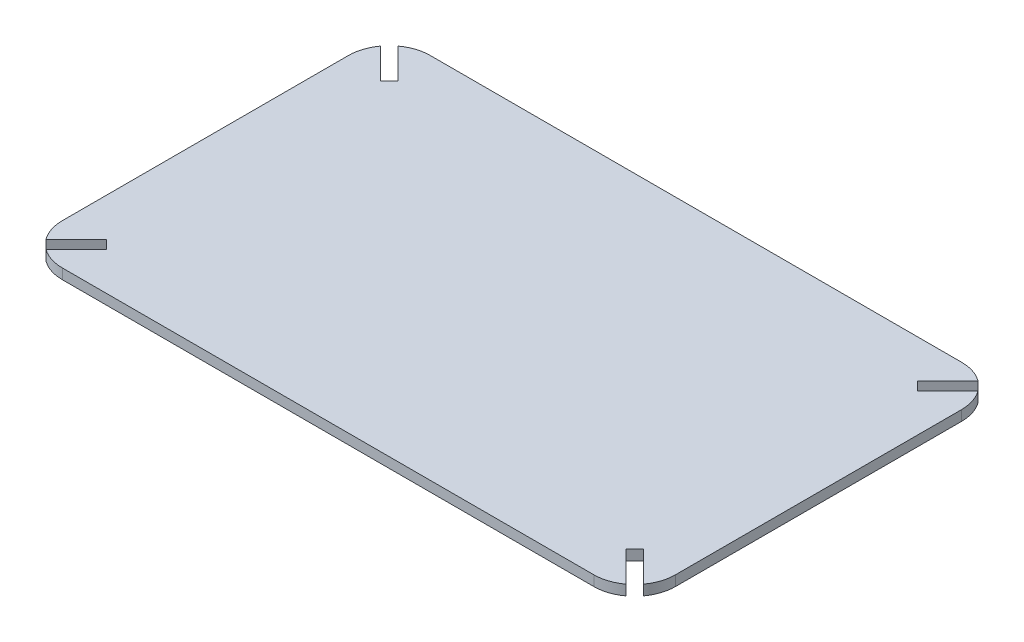
SolidWorks part; units mm, degrees
ref_plane "Front Plane" through (0, 0, 0) normal (0, 0, 1) x (1, 0, 0)
ref_plane "Top Plane" through (0, 0, 0) normal (0, 1, 0) x (1, 0, 0)
ref_plane "Right Plane" through (0, 0, 0) normal (1, 0, 0) x (0, 0, -1)
sketch "Sketch1" plane through (0, 0, 0) normal (0, 1, 0) x (1, 0, 0)
  line L1 (-165.1, -114.3) -> (165.1, -114.3)
  line L2 (-190.5, -88.9) -> (-190.5, 88.9)
  line L3 (-165.1, 114.3) -> (165.1, 114.3)
  line L4 (190.5, -88.9) -> (190.5, 88.9)
  line L5 (-190.5, -114.3) -> (190.5, 114.3) construction
  line L6 (-190.5, 114.3) -> (190.5, -114.3) construction
  arc A0 (-165.1, -114.3) -> (-190.5, -88.9) centre (-165.1, -88.9) cw
  arc A1 (165.1, -114.3) -> (190.5, -88.9) centre (165.1, -88.9) ccw
  arc A2 (165.1, 114.3) -> (190.5, 88.9) centre (165.1, 88.9) cw
  arc A3 (-190.5, 88.9) -> (-165.1, 114.3) centre (-165.1, 88.9) cw
  point P0 (0, 0)
  dimension "D3" = 25.4
  dimension "D1" = 228.6
  dimension "D2" = 381
extrude "Base Support" add sketch "Sketch1" along normal blind 6.35
sketch "Sketch2" plane through (0, 0, 0) normal (0, 1, 0) x (1, 0, 0)
  line L0 (-183.0605, -106.8605) -> (-190.996, -114.796) construction
  line L1 (-180.1632, -109.3514) -> (-161.3047, -90.4928)
  line L2 (-161.3047, -90.4928) -> (-166.6928, -85.1047)
  line L3 (-166.6928, -85.1047) -> (-185.5514, -103.9632)
  line L4 (0, 0) -> (0, -94.4406) construction
  line L5 (0, 0) -> (-78.1343, 0) construction
  line L6 (161.3047, -90.4928) -> (166.6928, -85.1047)
  line L7 (166.6928, -85.1047) -> (185.5514, -103.9632)
  line L8 (180.1632, -109.3514) -> (161.3047, -90.4928)
  line L9 (180.1632, 109.3514) -> (161.3047, 90.4928)
  line L10 (166.6928, 85.1047) -> (185.5514, 103.9632)
  line L11 (161.3047, 90.4928) -> (166.6928, 85.1047)
  line L12 (-166.6928, 85.1047) -> (-185.5514, 103.9632)
  line L13 (-161.3047, 90.4928) -> (-166.6928, 85.1047)
  line L14 (-180.1632, 109.3514) -> (-161.3047, 90.4928)
  arc A0 (-190.5, -88.9) -> (-165.1, -114.3) centre (-165.1, -88.9) ccw construction
  arc A1 (-185.5514, -103.9632) -> (-180.1632, -109.3514) centre (-165.1, -88.9) ccw
  arc A2 (185.5514, -103.9632) -> (180.1632, -109.3514) centre (165.1, -88.9) cw
  arc A3 (185.5514, 103.9632) -> (180.1632, 109.3514) centre (165.1, 88.9) ccw
  arc A4 (-185.5514, 103.9632) -> (-180.1632, 109.3514) centre (-165.1, 88.9) cw
  point P9 (-170.734, -99.9221)
  dimension "D1" = 7.62
  dimension "D2" = 3.81
  dimension "D3" = 26.67
extrude "Cut-Extrude1" cut sketch "Sketch2" along normal blind 6.35
